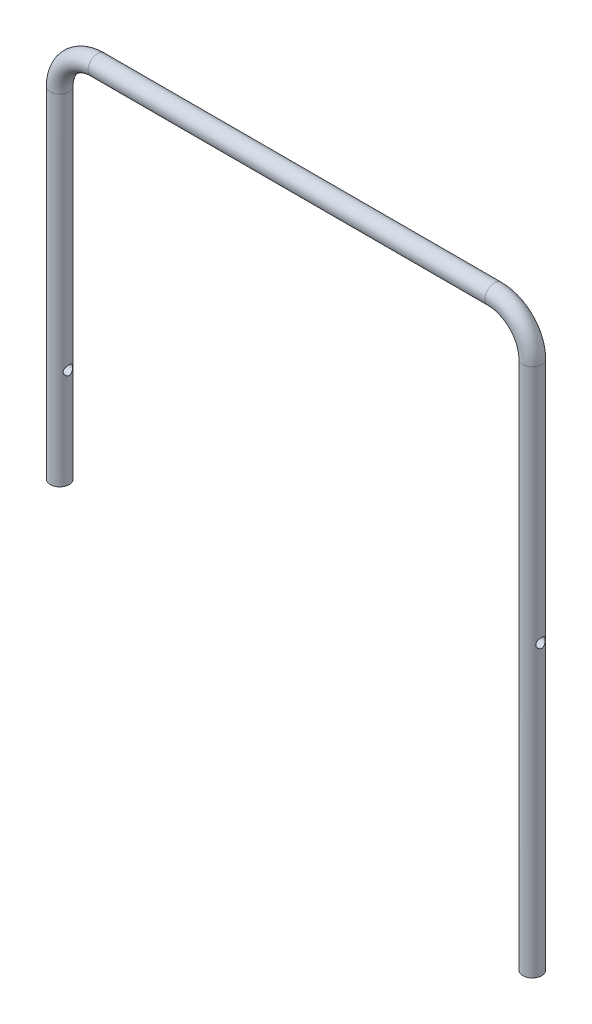
SolidWorks part; units mm, degrees
ref_plane "Alzado" through (0, 0, 0) normal (0, 0, 1) x (1, 0, 0)
ref_plane "Planta" through (0, 0, 0) normal (0, 1, 0) x (1, 0, 0)
ref_plane "Vista lateral" through (0, 0, 0) normal (1, 0, 0) x (0, 0, -1)
sketch "Croquis1" plane through (0, 0, 0) normal (0, 0, 1) x (1, 0, 0)
  line L0 (0, 0) -> (0, 180)
  line L1 (20, 200) -> (230, 200)
  line L2 (250, 180) -> (250, -100)
  arc A0 (230, 200) -> (250, 180) centre (230, 180) cw
  arc A1 (0, 180) -> (20, 200) centre (20, 180) cw
  point P7 (250, 200)
  point P10 (0, 200)
  dimension "D4" = 20
  dimension "D1" = 200
  dimension "D2" = 300
  dimension "D3" = 250
sketch "Croquis2" plane through (0, 0, 0) normal (0, 1, 0) x (1, 0, 0)
  circle A0 centre (0, 0) radius 5
  dimension "D1" = 10
sweep "Barrer1" add profiles "Croquis2" path "Croquis1"
sketch "Croquis4" plane through (0, 0, 0) normal (1, 0, 0) x (0, 0, -1)
  line L0 (0, -100) -> (0, 205) construction
  line L1 (-5, -100) -> (5, -100) construction
  circle A0 centre (0, 200) radius 5 construction
  circle A1 centre (0, 52.5) radius 2.5
  dimension "D1" = 5
extrude "Cortar-Extruir2" cut sketch "Croquis4" against normal through all both and the other way through all
